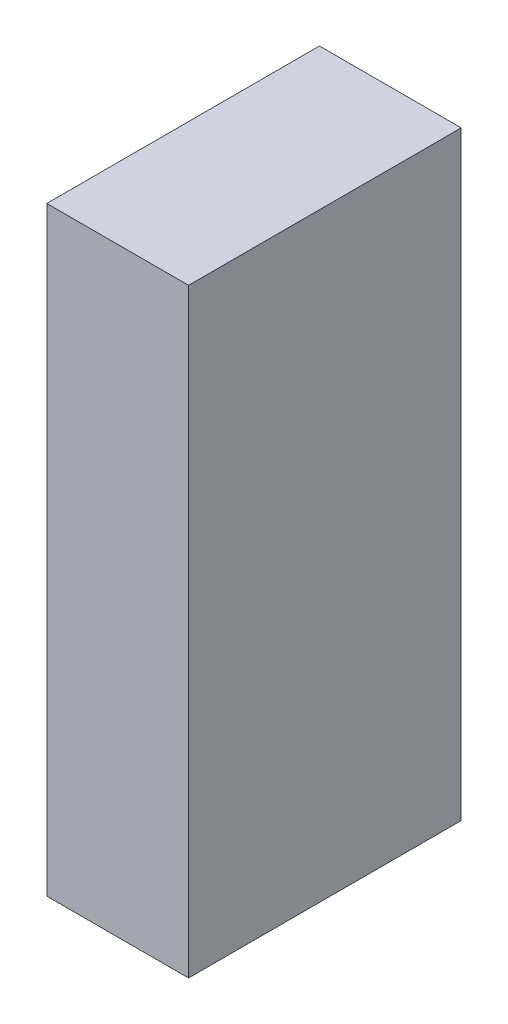
SolidWorks part; units mm, degrees
ref_plane "Спереди" through (0, 0, 0) normal (0, 0, 1) x (1, 0, 0)
ref_plane "Сверху" through (0, 0, 0) normal (0, 1, 0) x (1, 0, 0)
ref_plane "Справа" through (0, 0, 0) normal (1, 0, 0) x (0, 0, -1)
sketch "Эскиз1" plane through (0, 0, 0) normal (1, 0, 0) x (0, 0, -1)
  line L1 (25, -55) -> (-25, -55)
  line L2 (25, -55) -> (25, 55)
  line L3 (25, 55) -> (-25, 55)
  line L4 (-25, -55) -> (-25, 55)
  line L5 (25, -55) -> (-25, 55) construction
  line L6 (25, 55) -> (-25, -55) construction
  point P0 (0, 0)
  dimension "D1" = 110
  dimension "D2" = 50
extrude "Бобышка-Вытянуть1" add sketch "Эскиз1" along normal blind 26
